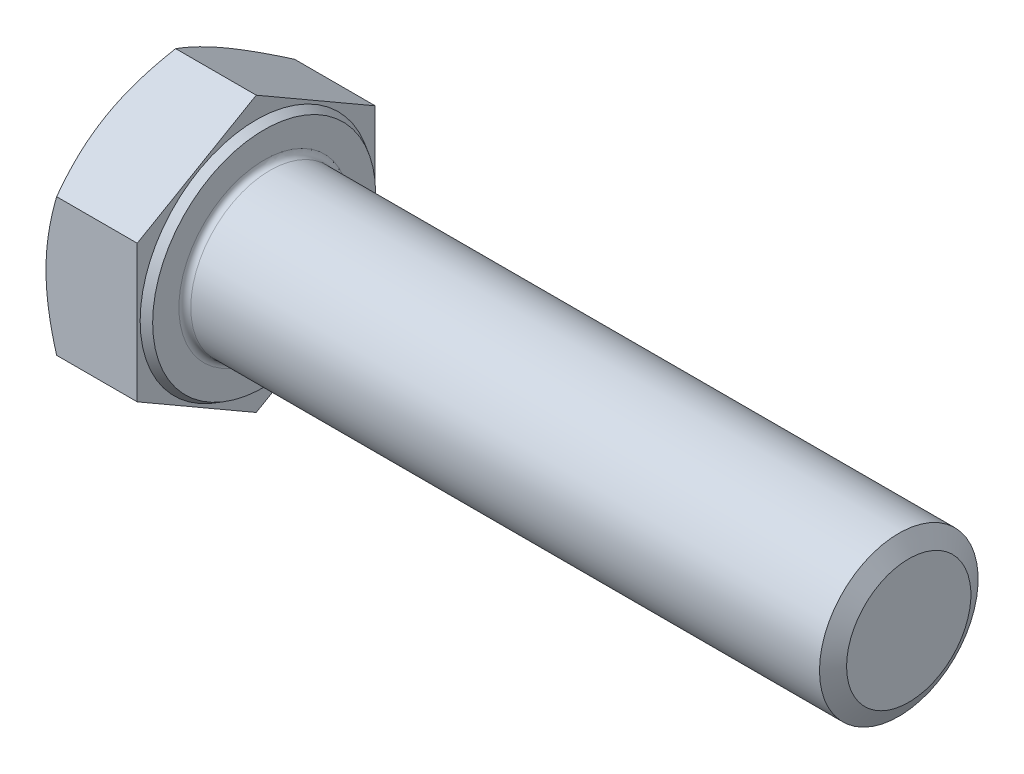
SolidWorks part; units mm, degrees
ref_plane "前视" through (0, 0, 0) normal (0, 0, 1) x (1, 0, 0)
ref_plane "上视" through (0, 0, 0) normal (0, 1, 0) x (1, 0, 0)
ref_plane "右视" through (0, 0, 0) normal (1, 0, 0) x (0, 0, -1)
sketch "草图1" plane through (0, 0, 0) normal (1, 0, 0) x (0, 0, -1)
  line L0 (12, 6.9282) -> (12, -6.9282)
  line L1 (-12, 6.9282) -> (-12, -6.9282)
  line L2 (12, -6.9282) -> (0, -13.8564)
  line L3 (0, -13.8564) -> (-12, -6.9282)
  line L4 (12, 6.9282) -> (0, 13.8564)
  line L5 (0, 13.8564) -> (-12, 6.9282)
  circle A0 centre (0, 0) radius 13.375 construction
  dimension "e" = 26.75
  dimension "s" = 24
  dimension "D2" = 120
  dimension "D3" = 12
  dimension "D4" = 12
  dimension "D5" = 12
extrude "基体-拉伸" add sketch "草图1" along normal blind 10
sketch "草图2" plane through (0, 0, 0) normal (0, 0, 1) x (1, 0, 0)
  line L0 (0, 6.9282) -> (0, -6.9282) construction
  line L1 (0, 0) -> (75, 0)
  line L2 (0, 0) -> (0, 8)
  line L3 (0, 8) -> (37, 8)
  line L4 (75, 0) -> (75, 6.268)
  line L5 (10, 13.8564) -> (10, 6.9282) construction
  line L7 (0, 0) -> (91, 0) construction
  line L8 (75, -6.268) -> (37, -8) construction
  line L9 (0, -8) -> (37, -8) construction
  line L10 (12, 8) -> (12, 0) construction
  line L11 (37, 15.24) -> (37, -1.27) construction
  line L12 (10, 6.9282) -> (10, -6.9282) construction
  line L13 (37, 8) -> (75, 8)
  line L14 (75, 8) -> (75, 6.268)
  dimension "l" = 65
  dimension "d" = 16
  dimension "Minor_dia" = 12.536
  dimension "p" = 2
  dimension "b" = 38
  dimension "ds" = 16
revolve "凸台-旋转1" add sketch "草图2" angle 360 about L7
cosmetic thread "螺旋线1" parameters "Thread_length"=38, "Thread_minor"=12.536
sketch "草图3" plane through (0, 0, 0) normal (0, 0, 1) x (1, 0, 0)
  line L0 (0, 12) -> (3.9585, 18.8564)
  line L1 (0, 13.8564) -> (0, 6.9282) construction
  line L2 (3.9585, 18.8564) -> (3.9585, 23.8564)
  line L3 (3.9585, 23.8564) -> (-10, 23.8564)
  line L4 (-10, 23.8564) -> (-10, 12)
  line L5 (-10, 12) -> (0, 12)
  line L6 (0, 0) -> (99.06, 0) construction
  line L7 (10, 13.8564) -> (0, 13.8564) construction
  dimension "D1" = 12
  dimension "D2" = 5
  dimension "D3" = 10
  dimension "D4" = 5
  dimension "Head_ch_ang" = 30
revolve "切除-旋转1" cut sketch "草图3" angle 360 about L6
sketch "草图4" plane through (0, 0, 0) normal (0, 0, 1) x (1, 0, 0)
  line L0 (10, 0) -> (10, 11.245) construction
  line L2 (10, -8) -> (10, 8) construction
  line L3 (10, 13.8564) -> (10, 6.9282) construction
  line L4 (10, 11.245) -> (9.2, 11.7069)
  line L5 (0, 0) -> (95.25, 0) construction
  line L6 (0, 0) -> (91, 0) construction
  line L9 (9.2, 11.7069) -> (9.2, 13.8564)
  line L10 (10, 13.8564) -> (1.0718, 13.8564) construction
  line L11 (9.2, 13.8564) -> (10, 13.8564)
  line L12 (10, 13.8564) -> (10, 11.245)
  dimension "D1" = 120
  dimension "c" = 0.8
  dimension "dw" = 22.49
revolve "切除-旋转3" cut sketch "草图4" angle 360 about L5
fillet "圆角" radius 0.6 1 edges at (10, 0, -8)
sketch "草图6" plane through (0, 0, 0) normal (0, 0, 1) x (1, 0, 0)
  line L0 (0, 0) -> (75, 0) construction
  line L1 (75, -8) -> (75, 8) construction
  line L2 (75, 0) -> (75, 8) construction
  line L4 (74, 8) -> (76, 8)
  line L5 (74, 8) -> (75, 6.2679)
  line L6 (75, 6.2679) -> (76, 8)
  dimension "D1" = 2
revolve "切除-旋转4" cut sketch "草图6" angle 360 about L0
pattern_linear "阵列(线性)1" [suppressed]
